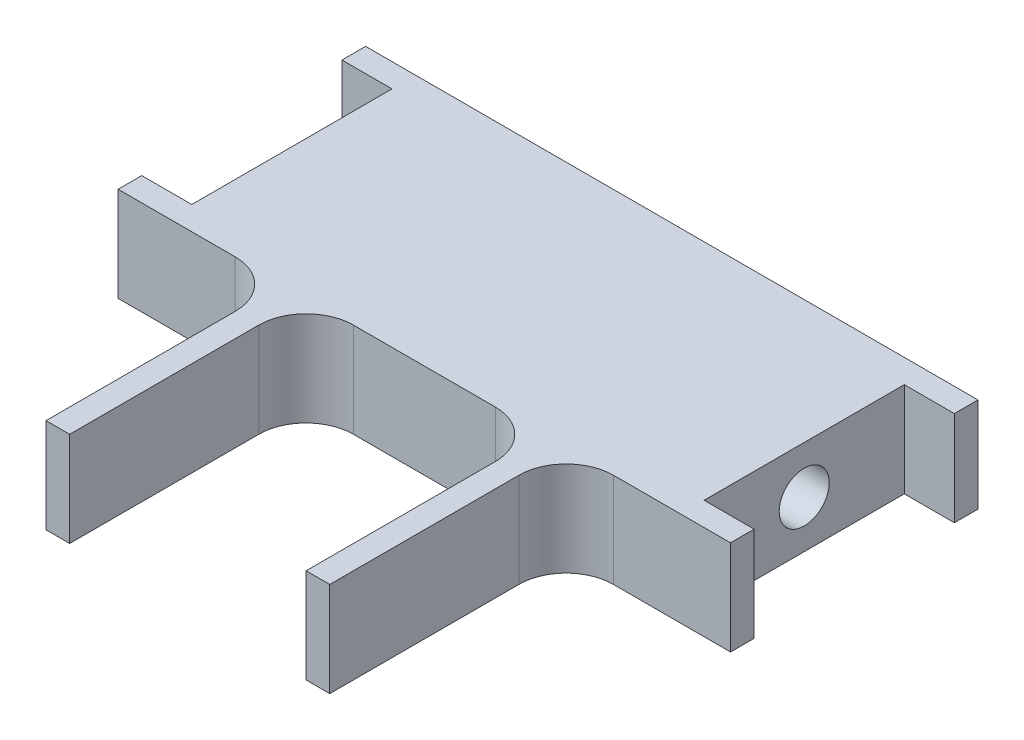
SolidWorks part; units mm, degrees
ref_plane "Front Plane" through (0, 0, 0) normal (0, 0, 1) x (1, 0, 0)
ref_plane "Top Plane" through (0, 0, 0) normal (0, 1, 0) x (1, 0, 0)
ref_plane "Right Plane" through (0, 0, 0) normal (1, 0, 0) x (0, 0, -1)
other "Configs"
sketch "Sketch1" plane through (0, 0, 0) normal (0, 1, 0) x (1, 0, 0)
  line L0 (0, 0) -> (0, 3)
  line L1 (0, 3) -> (6.35, 3)
  line L2 (6.35, 3) -> (6.35, 28.4)
  line L3 (6.35, 28.4) -> (0, 28.4)
  line L4 (0, 28.4) -> (0, 31.4)
  line L5 (0, 31.4) -> (77.7, 31.4)
  line L6 (77.7, 31.4) -> (77.7, 28.4)
  line L7 (77.7, 28.4) -> (71.35, 28.4)
  line L8 (71.35, 28.4) -> (71.35, 3)
  line L9 (71.35, 3) -> (77.7, 3)
  line L10 (77.7, 3) -> (77.7, 0)
  line L11 (77.7, 0) -> (0, 0)
  dimension "D1" = 6.35
  dimension "D2" = 25.4
  dimension "D3" = 3
  dimension "D4" = 65
extrude "Boss-Extrude1" add sketch "Sketch1" along normal blind 12
sketch "Sketch2" plane through (6.35, 0, 0) normal (-1, 0, 0) x (0, 0, 1)
  line L0 (-28.4, 12) -> (-3, 0) construction
  circle A0 centre (-15.7, 6) radius 3.175
  dimension "D1" = 6.35
extrude "Cut-Extrude1" cut sketch "Sketch2" against normal through all
sketch "Sketch3" plane through (0, 0, 0) normal (0, 0, 1) x (1, 0, 0)
  line L0 (0, 0) -> (77.7, 0) construction
  line L1 (20.85, 0) -> (23.85, 0)
  line L2 (20.85, 0) -> (20.85, 12)
  line L3 (20.85, 12) -> (23.85, 12)
  line L4 (23.85, 0) -> (23.85, 12)
  line L5 (0, 12) -> (77.7, 12) construction
  line L6 (23.85, 0) -> (38.85, 0) construction
  line L7 (53.85, 0) -> (56.85, 0)
  line L8 (53.85, 0) -> (53.85, 12)
  line L9 (53.85, 12) -> (56.85, 12)
  line L10 (56.85, 0) -> (56.85, 12)
  line L11 (38.85, 0) -> (53.85, 0) construction
  point P12 (38.85, 0)
  dimension "D1" = 3
  dimension "D2" = 30
extrude "Boss-Extrude2" add sketch "Sketch3" along normal blind 30
fillet "Fillet1" radius 6 4 edges at (53.85, 6, 0) (56.85, 6, 0)
